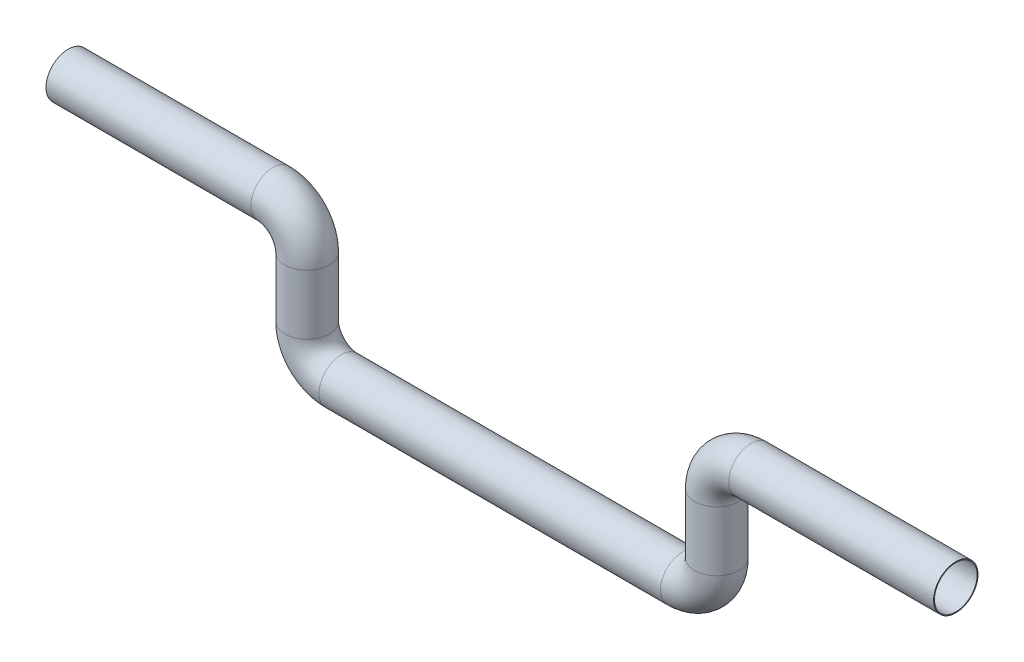
SolidWorks part; units mm, degrees
ref_plane "Front Plane" through (0, 0, 0) normal (0, 0, 1) x (1, 0, 0)
ref_plane "Top Plane" through (0, 0, 0) normal (0, 1, 0) x (1, 0, 0)
ref_plane "Right Plane" through (0, 0, 0) normal (1, 0, 0) x (0, 0, -1)
sketch "Sketch2" plane through (0, 0, 0) normal (0, 0, 1) x (1, 0, 0)
  line L0 (0, 0) -> (100, 0)
  line L1 (120, 20) -> (120, 55)
  line L2 (140, 75) -> (260, 75)
  arc A0 (100, 0) -> (120, 20) centre (100, 20) ccw
  arc A1 (120, 55) -> (140, 75) centre (140, 55) cw
  point P7 (120, 0)
  dimension "D4" = 20
  dimension "D1" = 260
  dimension "D2" = 120
  dimension "D3" = 75
ref_plane "Plane1" through (0, 0, 0) normal (1, 0, 0) x (0, 0, -1)
sketch "Sketch3" plane through (0, 0, 0) normal (1, 0, 0) x (0, 0, -1)
  circle A0 centre (0, 0) radius 12.5
  circle A1 centre (0, 0) radius 13
  dimension "D1" = 25
  dimension "D2" = 26
sweep "Sweep1" add profiles "Sketch3" path "Sketch2"
mirror "Mirror2" about plane through (0, 0, 0) normal (1, 0, 0) of bodies 101
